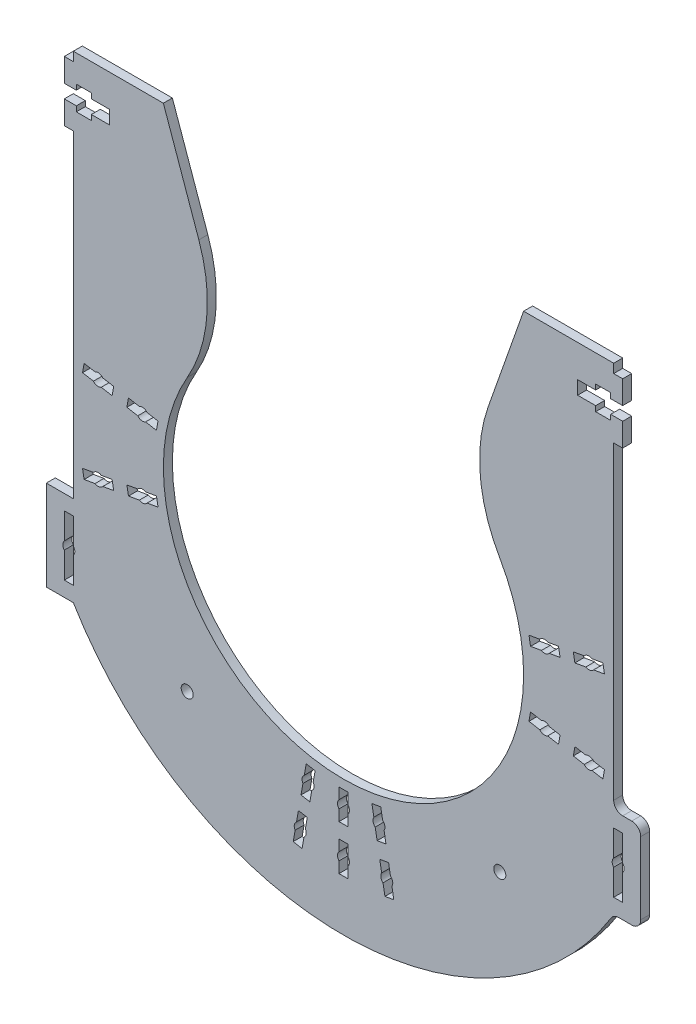
SolidWorks part; units mm, degrees
ref_plane "前视基准面" through (0, 0, 0) normal (0, 0, 1) x (1, 0, 0)
ref_plane "上视基准面" through (0, 0, 0) normal (0, 1, 0) x (1, 0, 0)
ref_plane "右视基准面" through (0, 0, 0) normal (1, 0, 0) x (0, 0, -1)
other "Configuration Table"
sketch "草图1" plane through (0, 0, 0) normal (0, 0, 1) x (1, 0, 0)
  line L0 (-60, 105) -> (-39.0475, 45.5554)
  line L1 (-90, 105) -> (-60, 105)
  line L2 (-90, 105) -> (-90, -105)
  line L3 (-90, -105) -> (90, -105)
  line L4 (90, 105) -> (90, -105)
  line L5 (-90, 105) -> (90, -105) construction
  line L6 (-90, -105) -> (90, 105) construction
  line L7 (39.0475, 45.5554) -> (60, 105)
  line L8 (60, 105) -> (90, 105)
  line L13 (0, -55) -> (0, 55) construction
  line L15 (-90, 105) -> (-93, 105)
  line L17 (90, 102) -> (93, 102)
  line L18 (90, 102) -> (90, 82)
  line L19 (90, 82) -> (93, 82)
  line L20 (93, 102) -> (93, 82)
  line L21 (-90, 102) -> (-93, 102)
  line L22 (-90, 102) -> (-90, 82)
  line L23 (-90, 82) -> (-93, 82)
  line L24 (-93, 102) -> (-93, 82)
  arc A0 (-39.0475, 45.5554) -> (39.0475, 45.5554) centre (0, 0) ccw
  arc A2 (-90, -54.0833) -> (90, -54.0833) centre (0, 0) ccw
  circle A3 centre (52.0633, -60.7405) radius 2
  circle A4 centre (-52.0633, -60.7405) radius 2
  point P0 (0, 0)
  point P12 (-60, 0)
  point P13 (60, 0)
  dimension "D3" = 120
  dimension "D7" = 4
  dimension "D8" = 4
  dimension "D9" = 80
  dimension "D10" = 20
  dimension "D1" = 210
  dimension "D2" = 180
  dimension "D4" = 3
  dimension "D5" = 3
  dimension "D11" = 3
  dimension "D12" = 20
  dimension "D13" = 3
extrude "凸台-拉伸1" add sketch "草图1" along normal mid plane 3
sketch "草图2" plane through (0, 0, 1.5) normal (0, 0, 1) x (1, 0, 0)
  line L0 (0, -1000) -> (0, 49000) construction
  line L1 (-1.5, -69.3229) -> (-1.5, -73)
  line L2 (-1.5, -63) -> (1.5, -63)
  line L3 (-1.5, -63) -> (-1.5, -66.6771)
  line L4 (-1.5, -73) -> (1.5, -73)
  line L5 (1.5, -63) -> (1.5, -66.6771)
  line L6 (-1.5, -63) -> (1.5, -73) construction
  line L7 (-1.5, -73) -> (1.5, -63) construction
  line L8 (-1.5, -78) -> (1.5, -78)
  line L9 (-1.5, -78) -> (-1.5, -81.6771)
  line L10 (-1.5, -88) -> (1.5, -88)
  line L11 (1.5, -78) -> (1.5, -81.6771)
  line L12 (-1.5, -78) -> (1.5, -88) construction
  line L13 (-1.5, -88) -> (1.5, -78) construction
  line L14 (1.5, -69.3229) -> (1.5, -73)
  line L15 (-1.5, -84.3229) -> (-1.5, -88)
  line L16 (1.5, -84.3229) -> (1.5, -88)
  line L17 (-84.3229, -1.5) -> (-88, -1.5)
  line L18 (-88, 1.5) -> (-88, -1.5)
  line L19 (-84.3229, 1.5) -> (-88, 1.5)
  line L20 (-78, 1.5) -> (-81.6771, 1.5)
  line L21 (-78, 1.5) -> (-78, -1.5)
  line L22 (-78, -1.5) -> (-81.6771, -1.5)
  line L23 (-63, 1.5) -> (-66.6771, 1.5)
  line L24 (-69.3229, 1.5) -> (-73, 1.5)
  line L25 (-73, 1.5) -> (-73, -1.5)
  line L26 (-69.3229, -1.5) -> (-73, -1.5)
  line L27 (-63, -1.5) -> (-66.6771, -1.5)
  line L28 (-63, 1.5) -> (-63, -1.5)
  line L29 (-1.5, 84.3229) -> (-1.5, 88)
  line L30 (1.5, 88) -> (-1.5, 88)
  line L31 (1.5, 84.3229) -> (1.5, 88)
  line L32 (1.5, 78) -> (1.5, 81.6771)
  line L33 (1.5, 78) -> (-1.5, 78)
  line L34 (-1.5, 78) -> (-1.5, 81.6771)
  line L35 (1.5, 63) -> (1.5, 66.6771)
  line L36 (1.5, 69.3229) -> (1.5, 73)
  line L37 (1.5, 73) -> (-1.5, 73)
  line L38 (-1.5, 69.3229) -> (-1.5, 73)
  line L39 (-1.5, 63) -> (-1.5, 66.6771)
  line L40 (1.5, 63) -> (-1.5, 63)
  line L41 (84.3229, 1.5) -> (88, 1.5)
  line L42 (88, -1.5) -> (88, 1.5)
  line L43 (84.3229, -1.5) -> (88, -1.5)
  line L44 (78, -1.5) -> (81.6771, -1.5)
  line L45 (78, -1.5) -> (78, 1.5)
  line L46 (78, 1.5) -> (81.6771, 1.5)
  line L47 (63, -1.5) -> (66.6771, -1.5)
  line L48 (69.3229, -1.5) -> (73, -1.5)
  line L49 (73, -1.5) -> (73, 1.5)
  line L50 (69.3229, 1.5) -> (73, 1.5)
  line L51 (63, 1.5) -> (66.6771, 1.5)
  line L52 (63, -1.5) -> (63, 1.5)
  line L53 (0, 0) -> (1.5, -63) construction
  line L54 (-83.3023, 13.1653) -> (-86.9236, 13.8038)
  line L55 (-86.4026, 16.7583) -> (-86.9236, 13.8038)
  line L56 (-82.7813, 16.1197) -> (-86.4026, 16.7583)
  line L57 (-76.5545, 15.0218) -> (-80.1758, 15.6603)
  line L58 (-76.5545, 15.0218) -> (-77.0755, 12.0673)
  line L59 (-77.0755, 12.0673) -> (-80.6967, 12.7059)
  line L60 (-61.7824, 12.417) -> (-65.4037, 13.0556)
  line L61 (-68.0092, 13.515) -> (-71.6305, 14.1535)
  line L62 (-71.6305, 14.1535) -> (-72.1514, 11.1991)
  line L63 (-68.5302, 10.5606) -> (-72.1514, 11.1991)
  line L64 (-62.3034, 9.4626) -> (-65.9246, 10.1011)
  line L65 (-61.7824, 12.417) -> (-62.3034, 9.4626)
  line L66 (61.7824, -12.417) -> (65.4037, -13.0556)
  line L67 (68.0092, -13.515) -> (71.6305, -14.1535)
  line L68 (71.6305, -14.1535) -> (72.1514, -11.1991)
  line L69 (68.5302, -10.5606) -> (72.1514, -11.1991)
  line L70 (62.3034, -9.4626) -> (65.9246, -10.1011)
  line L71 (61.7824, -12.417) -> (62.3034, -9.4626)
  line L72 (83.3023, -13.1653) -> (86.9236, -13.8038)
  line L73 (86.4026, -16.7583) -> (86.9236, -13.8038)
  line L74 (82.7813, -16.1197) -> (86.4026, -16.7583)
  line L75 (76.5545, -15.0218) -> (80.1758, -15.6603)
  line L76 (76.5545, -15.0218) -> (77.0755, -12.0673)
  line L77 (77.0755, -12.0673) -> (80.6967, -12.7059)
  line L78 (-12.417, -61.7824) -> (-13.0556, -65.4037)
  line L79 (-13.515, -68.0092) -> (-14.1535, -71.6305)
  line L80 (-14.1535, -71.6305) -> (-11.1991, -72.1514)
  line L81 (-10.5606, -68.5302) -> (-11.1991, -72.1514)
  line L82 (-9.4626, -62.3034) -> (-10.1011, -65.9246)
  line L83 (-12.417, -61.7824) -> (-9.4626, -62.3034)
  line L84 (-13.1653, -83.3023) -> (-13.8038, -86.9236)
  line L85 (-16.7583, -86.4026) -> (-13.8038, -86.9236)
  line L86 (-16.1197, -82.7813) -> (-16.7583, -86.4026)
  line L87 (-15.0218, -76.5545) -> (-15.6603, -80.1758)
  line L88 (-15.0218, -76.5545) -> (-12.0673, -77.0755)
  line L89 (-12.0673, -77.0755) -> (-12.7059, -80.6967)
  line L90 (-77.0755, -12.0673) -> (-80.6967, -12.7059)
  line L91 (-76.5545, -15.0218) -> (-77.0755, -12.0673)
  line L92 (-76.5545, -15.0218) -> (-80.1758, -15.6603)
  line L93 (-82.7813, -16.1197) -> (-86.4026, -16.7583)
  line L94 (-86.4026, -16.7583) -> (-86.9236, -13.8038)
  line L95 (-83.3023, -13.1653) -> (-86.9236, -13.8038)
  line L96 (-61.7824, -12.417) -> (-62.3034, -9.4626)
  line L97 (-62.3034, -9.4626) -> (-65.9246, -10.1011)
  line L98 (-68.5302, -10.5606) -> (-72.1514, -11.1991)
  line L99 (-71.6305, -14.1535) -> (-72.1514, -11.1991)
  line L100 (-68.0092, -13.515) -> (-71.6305, -14.1535)
  line L101 (-61.7824, -12.417) -> (-65.4037, -13.0556)
  line L102 (12.0673, -77.0755) -> (12.7059, -80.6967)
  line L103 (15.0218, -76.5545) -> (12.0673, -77.0755)
  line L104 (15.0218, -76.5545) -> (15.6603, -80.1758)
  line L105 (16.1197, -82.7813) -> (16.7583, -86.4026)
  line L106 (16.7583, -86.4026) -> (13.8038, -86.9236)
  line L107 (13.1653, -83.3023) -> (13.8038, -86.9236)
  line L108 (12.417, -61.7824) -> (9.4626, -62.3034)
  line L109 (9.4626, -62.3034) -> (10.1011, -65.9246)
  line L110 (10.5606, -68.5302) -> (11.1991, -72.1514)
  line L111 (14.1535, -71.6305) -> (11.1991, -72.1514)
  line L112 (13.515, -68.0092) -> (14.1535, -71.6305)
  line L113 (12.417, -61.7824) -> (13.0556, -65.4037)
  line L114 (61.7824, 12.417) -> (62.3034, 9.4626)
  line L115 (62.3034, 9.4626) -> (65.9246, 10.1011)
  line L116 (68.5302, 10.5606) -> (72.1514, 11.1991)
  line L117 (71.6305, 14.1535) -> (72.1514, 11.1991)
  line L118 (68.0092, 13.515) -> (71.6305, 14.1535)
  line L119 (61.7824, 12.417) -> (65.4037, 13.0556)
  line L120 (77.0755, 12.0673) -> (80.6967, 12.7059)
  line L121 (76.5545, 15.0218) -> (77.0755, 12.0673)
  line L122 (76.5545, 15.0218) -> (80.1758, 15.6603)
  line L123 (82.7813, 16.1197) -> (86.4026, 16.7583)
  line L124 (86.4026, 16.7583) -> (86.9236, 13.8038)
  line L125 (83.3023, 13.1653) -> (86.9236, 13.8038)
  arc A0 (-39.0475, 45.5554) -> (39.0475, 45.5554) centre (0, 0) ccw construction
  arc A1 (-1.5, -66.6771) -> (-1.5, -69.3229) centre (0, -68) ccw
  arc A2 (1.5, -84.3229) -> (1.5, -81.6771) centre (0, -83) ccw
  arc A3 (1.5, -69.3229) -> (1.5, -66.6771) centre (0, -68) ccw
  arc A4 (-1.5, -81.6771) -> (-1.5, -84.3229) centre (0, -83) ccw
  arc A5 (-81.6771, 1.5) -> (-84.3229, 1.5) centre (-83, 0) ccw
  arc A6 (-84.3229, -1.5) -> (-81.6771, -1.5) centre (-83, 0) ccw
  arc A7 (-66.6771, 1.5) -> (-69.3229, 1.5) centre (-68, 0) ccw
  arc A8 (-69.3229, -1.5) -> (-66.6771, -1.5) centre (-68, 0) ccw
  arc A9 (1.5, 81.6771) -> (1.5, 84.3229) centre (0, 83) ccw
  arc A10 (-1.5, 84.3229) -> (-1.5, 81.6771) centre (0, 83) ccw
  arc A11 (1.5, 66.6771) -> (1.5, 69.3229) centre (0, 68) ccw
  arc A12 (-1.5, 69.3229) -> (-1.5, 66.6771) centre (0, 68) ccw
  arc A13 (81.6771, -1.5) -> (84.3229, -1.5) centre (83, 0) ccw
  arc A14 (84.3229, 1.5) -> (81.6771, 1.5) centre (83, 0) ccw
  arc A15 (66.6771, -1.5) -> (69.3229, -1.5) centre (68, 0) ccw
  arc A16 (69.3229, 1.5) -> (66.6771, 1.5) centre (68, 0) ccw
  arc A17 (-80.1758, 15.6603) -> (-82.7813, 16.1197) centre (-81.739, 14.4128) ccw
  arc A18 (-83.3023, 13.1653) -> (-80.6967, 12.7059) centre (-81.739, 14.4128) ccw
  arc A19 (-65.4037, 13.0556) -> (-68.0092, 13.515) centre (-66.9669, 11.8081) ccw
  arc A20 (-68.5302, 10.5606) -> (-65.9246, 10.1011) centre (-66.9669, 11.8081) ccw
  arc A21 (65.4037, -13.0556) -> (68.0092, -13.515) centre (66.9669, -11.8081) ccw
  arc A22 (68.5302, -10.5606) -> (65.9246, -10.1011) centre (66.9669, -11.8081) ccw
  arc A23 (80.1758, -15.6603) -> (82.7813, -16.1197) centre (81.739, -14.4128) ccw
  arc A24 (83.3023, -13.1653) -> (80.6967, -12.7059) centre (81.739, -14.4128) ccw
  arc A25 (-13.0556, -65.4037) -> (-13.515, -68.0092) centre (-11.8081, -66.9669) ccw
  arc A26 (-10.5606, -68.5302) -> (-10.1011, -65.9246) centre (-11.8081, -66.9669) ccw
  arc A27 (-15.6603, -80.1758) -> (-16.1197, -82.7813) centre (-14.4128, -81.739) ccw
  arc A28 (-13.1653, -83.3023) -> (-12.7059, -80.6967) centre (-14.4128, -81.739) ccw
  arc A29 (-83.3023, -13.1653) -> (-80.6967, -12.7059) centre (-81.739, -14.4128) cw
  arc A30 (-80.1758, -15.6603) -> (-82.7813, -16.1197) centre (-81.739, -14.4128) cw
  arc A31 (-68.5302, -10.5606) -> (-65.9246, -10.1011) centre (-66.9669, -11.8081) cw
  arc A32 (-65.4037, -13.0556) -> (-68.0092, -13.515) centre (-66.9669, -11.8081) cw
  arc A33 (13.1653, -83.3023) -> (12.7059, -80.6967) centre (14.4128, -81.739) cw
  arc A34 (15.6603, -80.1758) -> (16.1197, -82.7813) centre (14.4128, -81.739) cw
  arc A35 (10.5606, -68.5302) -> (10.1011, -65.9246) centre (11.8081, -66.9669) cw
  arc A36 (13.0556, -65.4037) -> (13.515, -68.0092) centre (11.8081, -66.9669) cw
  arc A37 (68.5302, 10.5606) -> (65.9246, 10.1011) centre (66.9669, 11.8081) cw
  arc A38 (65.4037, 13.0556) -> (68.0092, 13.515) centre (66.9669, 11.8081) cw
  arc A39 (83.3023, 13.1653) -> (80.6967, 12.7059) centre (81.739, 14.4128) cw
  arc A40 (80.1758, 15.6603) -> (82.7813, 16.1197) centre (81.739, 14.4128) cw
  point P1 (0, -68)
  point P8 (0, -83)
  point P13 (0, -60)
  point P18 (0, -73)
  point P143 (0, 0)
  dimension "D7" = 4
  dimension "D8" = 4
  dimension "D1" = 10
  dimension "D2" = 3
  dimension "D3" = 10
  dimension "D4" = 3
  dimension "D5" = 3
  dimension "D6" = 5
  dimension "D10" = 2
  dimension "D11" = 10
  dimension "D9" = 4
extrude "切除-拉伸1" cut sketch "草图2" against normal through all contours A30 L92 L91 L90 A29 L95 L94 L93 | A32 L101 L96 L97 A31 L98 L99 L100 | L63 A20 L64 L65 L60 A19 L61 L62 | L54 A18 L59 L58 L57 A17 L56 L55 | L72 A24 L77 L76 L75 A23 L74 L73 | L69 A22 L70 L71 L66 A21 L67 L68 | A38 L119 L114 L115 A37 L116 L117 L118 | A34 L104 L103 L102 A33 L107 L106 L105 | A36 L113 L108 L109 A35 L110 L111 L112 | L9 A4 L15 L10 L16 A2 L11 L8 | L14 A3 L5 L2 L3 A1 L1 L4 | L81 A26 L82 L83 L78 A25 L79 L80 | L84 A28 L89 L88 L87 A27 L86 L85 | L122 A40 L123 L124 L125 A39 L120 L121
fillet "圆角1" radius 50 2 edges at (39.0475, 45.5554, 0) (-39.0475, 45.5554, 0)
sketch "草图3" plane through (0, 0, 1.5) normal (0, 0, 1) x (1, 0, 0)
  line L0 (90, -29.0833) -> (93, -49.0833) construction
  line L1 (90, -54.0833) -> (99, -54.0833)
  line L2 (90, -54.0833) -> (90, -24.0833)
  line L3 (90, -24.0833) -> (99, -24.0833)
  line L4 (99, -54.0833) -> (99, -24.0833)
  line L5 (90, -49.0833) -> (93, -49.0833)
  line L6 (90, -49.0833) -> (90, -29.0833)
  line L7 (90, -29.0833) -> (93, -29.0833)
  line L8 (93, -49.0833) -> (93, -29.0833)
  circle A0 centre (91.5, -39.0833) radius 2
  dimension "D6" = 4
  dimension "D1" = 30
  dimension "D2" = 9
  dimension "D3" = 20
  dimension "D4" = 3
  dimension "D5" = 5
extrude "凸台-拉伸2" add sketch "草图3" against normal blind 3 contours A0 L8 L5 L2 L1 L4 L3 L7
fillet "圆角2" radius 3 4 edges at (90, -54.0833, 0) (90, -24.0833, 0) (99, -24.0833, 0) (99, -54.0833, 0)
mirror "镜向1" about plane through (0, 0, 0) normal (1, 0, 0) of "凸台-拉伸2"
sketch "草图6" plane through (0, 0, -1.5) normal (0, 0, -1) x (-1, 0, 0)
  line L0 (-93, 102) -> (-93, 82) construction
  line L1 (-78, 89.75) -> (-93, 89.75)
  line L2 (-78, 89.75) -> (-78, 94.25)
  line L3 (-78, 94.25) -> (-93, 94.25)
  line L4 (-93, 89.75) -> (-93, 94.25)
  line L5 (-78, 89.75) -> (-93, 94.25) construction
  line L6 (-78, 94.25) -> (-93, 89.75) construction
  line L7 (-90, 102) -> (-93, 102) construction
  line L8 (-84, 88) -> (-89, 88)
  line L9 (-84, 88) -> (-84, 96)
  line L10 (-84, 96) -> (-89, 96)
  line L11 (-89, 88) -> (-89, 96)
  line L12 (-84, 88) -> (-89, 96) construction
  line L13 (-84, 96) -> (-89, 88) construction
  line L14 (-90, 105) -> (-90, 102) construction
  line L15 (0, 1.65) -> (0, -1.65) construction
  line L16 (84, 96) -> (89, 96)
  line L17 (89, 88) -> (89, 96)
  line L18 (84, 88) -> (89, 88)
  line L19 (84, 88) -> (84, 96)
  line L20 (78, 94.25) -> (93, 94.25)
  line L21 (93, 89.75) -> (93, 94.25)
  line L22 (78, 89.75) -> (93, 89.75)
  line L23 (78, 89.75) -> (78, 94.25)
  point P0 (-85.5, 92)
  point P7 (-86.5, 92)
  dimension "D1" = 10
  dimension "D2" = 15
  dimension "D3" = 4.5
  dimension "D4" = 5
  dimension "D5" = 8
  dimension "D6" = 1
extrude "切除-拉伸2" cut sketch "草图6" against normal through all contours L11 L8 L9 L1 | L11 L1 L9 L3 | L11 L3 L9 L10 | L9 L1 L2 L3 | L1 L11 L3 L4 | L17 L22 L21 L20 | L19 L22 L17 L20 | L19 L20 L17 L16 | L22 L19 L18 L17 | L23 L22 L19 L20
sketch "草图8" plane through (0, 0, 1.5) normal (0, 0, 1) x (1, 0, 0)
  circle A0 centre (-91.5, -39.0833) radius 2
  circle A1 centre (91.5, -39.0833) radius 2
extrude "切除-拉伸4" cut sketch "草图8" against normal blind 10
